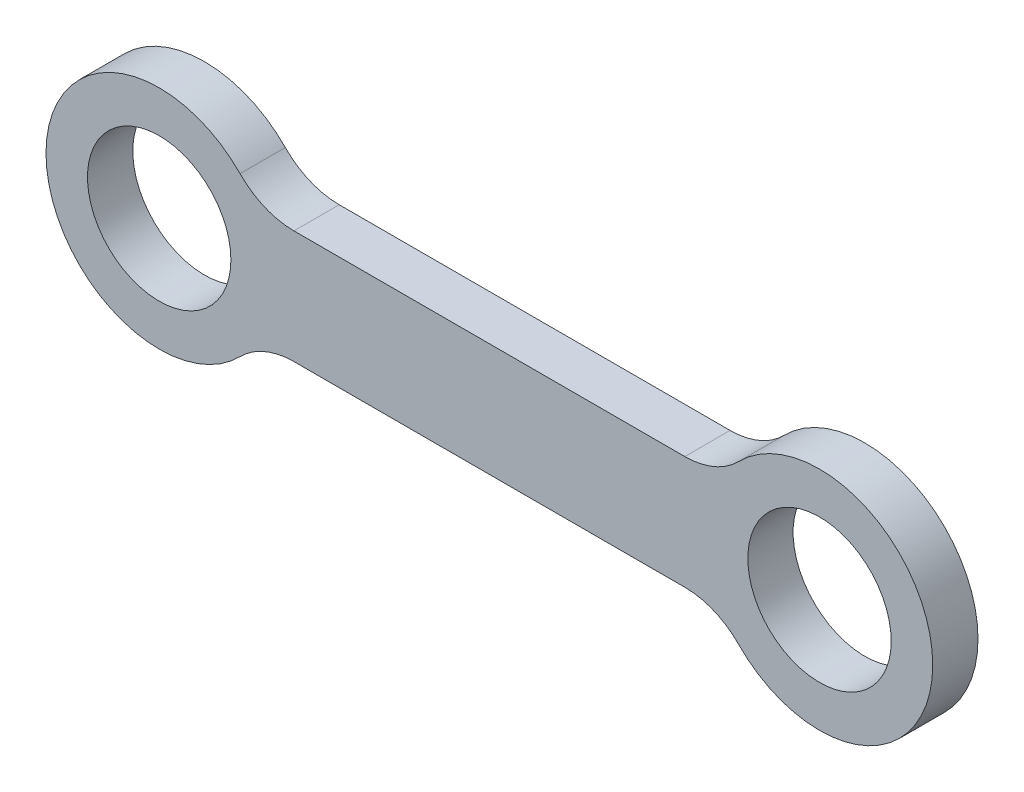
SolidWorks part; units mm, degrees
ref_plane "Płaszczyzna przednia" through (0, 0, 0) normal (0, 0, 1) x (1, 0, 0)
ref_plane "Płaszczyzna górna" through (0, 0, 0) normal (0, 1, 0) x (1, 0, 0)
ref_plane "Płaszczyzna prawa" through (0, 0, 0) normal (1, 0, 0) x (0, 0, -1)
other "tab"
sketch "Szkic1" plane through (0, 0, 0) normal (0, 0, 1) x (1, 0, 0)
  line L0 (-74.5096, 7.5) -> (-12.9904, 7.5)
  line L8 (-74.5096, -7.5) -> (-12.9904, -7.5)
  line L10 (0, 0) -> (-20.2282, 0) construction
  circle A0 centre (0, 0) radius 9.5
  circle A1 centre (-87.5, 0) radius 9.5
  arc A4 (-74.5096, 7.5) -> (-100.5, -7.4833) centre (-87.5, 0) ccw
  arc A6 (12.9904, -7.5) -> (-12.9904, 7.5) centre (0, 0) ccw
  arc A7 (-12.9904, -7.5) -> (12.9904, -7.5) centre (0, 0) ccw
  circle A8 centre (-87.5, 0) radius 15 construction
  arc A10 (-100.5, -7.4833) -> (-74.5096, -7.5) centre (-87.5, 0) ccw
  point P0 (0, 0)
  dimension "D3" = 87.5
  dimension "D6" = 19
  dimension "D8" = 15
  dimension "D1" = 15
  dimension "D2" = 19
  dimension "D7" = 15
extrude "Dodanie-wyciągnięcie1" add sketch "Szkic1" along normal mid plane 6
fillet "Zaokrąglenie1" radius 10 4 edges at (-12.9904, -7.5, 0) (-74.5096, -7.5, 0) (-12.9904, 7.5, 0) (-74.5096, 7.5, 0)
